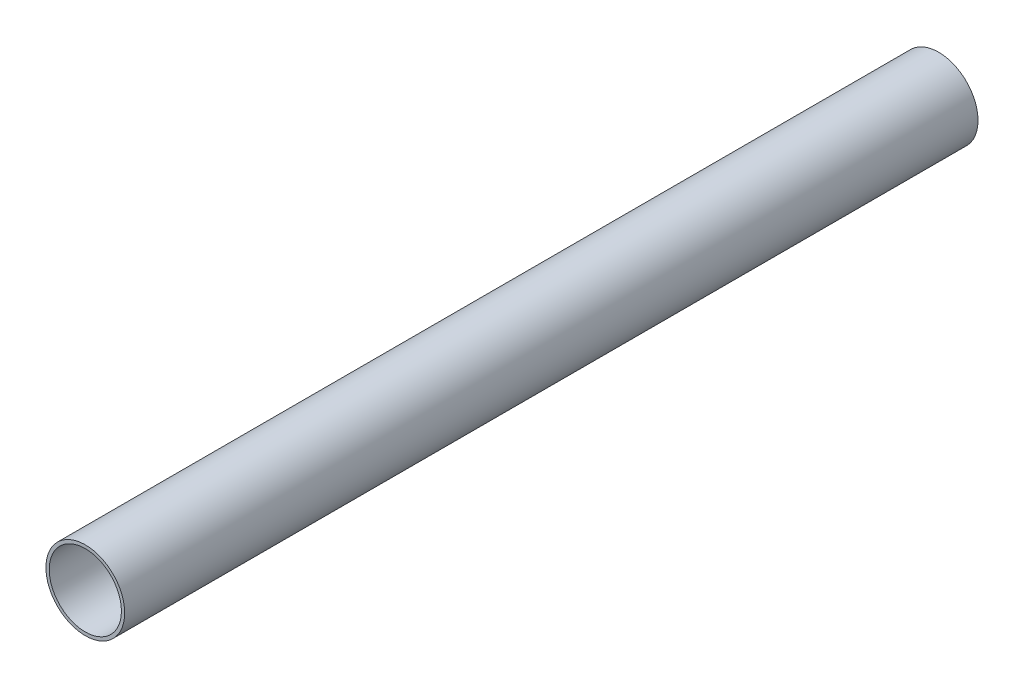
SolidWorks part; units mm, degrees
material "Karbon Fiber Boru "
ref_plane "Ön Düzlem" through (0, 0, 0) normal (0, 0, 1) x (1, 0, 0)
ref_plane "Üst Düzlem" through (0, 0, 0) normal (0, 1, 0) x (1, 0, 0)
ref_plane "Sağ Düzlem" through (0, 0, 0) normal (1, 0, 0) x (0, 0, -1)
sketch "Çizim1" plane through (0, 0, 0) normal (0, 0, 1) x (1, 0, 0)
  circle A0 centre (0, 0) radius 12
  circle A1 centre (0, 0) radius 11
  dimension "D1" = 24
  dimension "D2" = 22
extrude "Yükseklik-Ekstrüzyon1" add sketch "Çizim1" along normal blind 260
